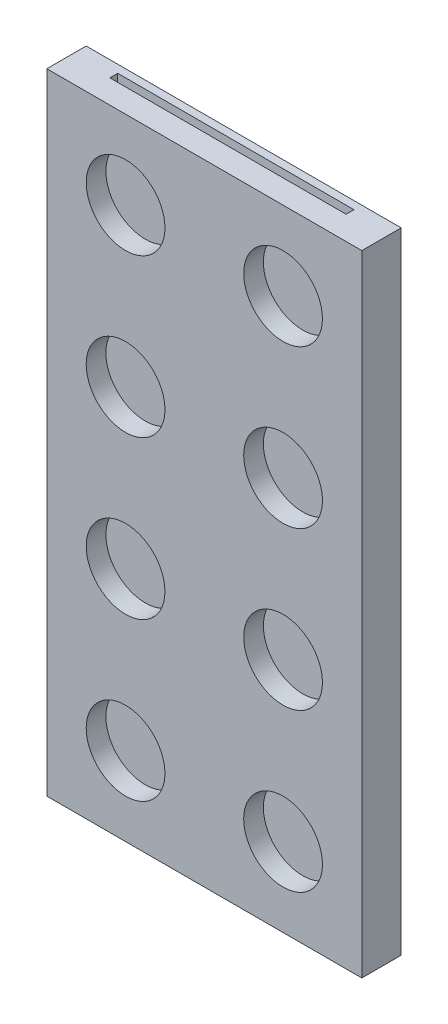
SolidWorks part; units mm, degrees
ref_plane "Front Plane" through (0, 0, 0) normal (0, 0, 1) x (1, 0, 0)
ref_plane "Top Plane" through (0, 0, 0) normal (0, 1, 0) x (1, 0, 0)
ref_plane "Right Plane" through (0, 0, 0) normal (1, 0, 0) x (0, 0, -1)
sketch "Sketch1" plane through (0, 0, 0) normal (0, 0, 1) x (1, 0, 0)
  line L1 (0, 0) -> (50.8, 0)
  line L2 (0, 0) -> (0, 101.6)
  line L3 (0, 101.6) -> (50.8, 101.6)
  line L4 (50.8, 0) -> (50.8, 101.6)
  dimension "D1" = 101.6
  dimension "D2" = 50.8
extrude "Boss-Extrude1" add sketch "Sketch1" along normal blind 6.35
sketch "Sketch3" plane through (0, 0, 6.35) normal (0, 0, 1) x (1, 0, 0)
  line L0 (0, 101.6) -> (0, 0) construction
  line L1 (50.8, 101.6) -> (0, 101.6) construction
  line L2 (0, 0) -> (50.8, 0) construction
  line L3 (25.4, 101.6) -> (25.4, 0)
  line L5 (12.7, 152.4) -> (12.7, 0)
  line L6 (38.1, 101.6) -> (38.1, 0)
  line L7 (50.8, 101.6) -> (50.8, 0)
  line L8 (63.5, 101.6) -> (63.5, 0)
  line L9 (76.2, 101.6) -> (76.2, 0)
  line L10 (88.9, 101.6) -> (88.9, 0)
  line L11 (0, 12.7) -> (50.8, 12.7)
  line L12 (50.8, 0) -> (50.8, 101.6) construction
  line L13 (0, 25.4) -> (50.8, 25.4)
  line L14 (0, 38.1) -> (50.8, 38.1)
  line L15 (0, 50.8) -> (50.8, 50.8)
  line L16 (0, 63.5) -> (50.8, 63.5)
  line L17 (0, 63.6141) -> (50.8, 63.6141)
  line L18 (0, 76.2) -> (50.8, 76.2)
  line L19 (0, 88.9) -> (50.8, 88.9)
  line L20 (0, 101.6) -> (50.8, 101.6)
  line L21 (0, 114.3) -> (50.8, 114.3)
  line L22 (0, 127) -> (50.8, 127)
  line L23 (0, 139.7) -> (50.8, 139.7)
  circle A0 centre (12.7, 139.7) radius 6.35
  circle A2 centre (38.1, 139.7) radius 6.35
  circle A4 centre (63.5, 139.7) radius 2.54
  circle A6 centre (88.9, 139.7) radius 2.54
  circle A7 centre (88.9, 114.3) radius 2.54
  circle A8 centre (63.5, 114.3) radius 2.54
  circle A9 centre (38.1, 114.3) radius 6.35
  circle A10 centre (12.7, 114.3) radius 6.35
  circle A11 centre (88.9, 88.9) radius 2.54
  circle A12 centre (63.5, 88.9) radius 2.54
  circle A13 centre (38.1, 88.9) radius 6.35
  circle A14 centre (12.7, 88.9) radius 6.35
  circle A15 centre (88.9, 63.5) radius 2.54
  circle A16 centre (63.5, 63.5) radius 2.54
  circle A17 centre (38.1, 63.5) radius 6.35
  circle A18 centre (12.7, 63.5) radius 6.35
  circle A19 centre (88.9, 38.1) radius 2.54
  circle A20 centre (63.5, 38.1) radius 2.54
  circle A21 centre (38.1, 38.1) radius 6.35
  circle A22 centre (12.7, 38.1) radius 6.35
  circle A23 centre (88.9, 12.7) radius 2.54
  circle A24 centre (63.5, 12.7) radius 2.54
  circle A25 centre (38.1, 12.7) radius 6.35
  circle A26 centre (12.7, 12.7) radius 6.35
  dimension "D1" = 12.7
  dimension "D2" = 12.7
  dimension "D3" = 12.7
  dimension "D4" = 12.7
  dimension "D5" = 12.7
  dimension "D6" = 12.7
  dimension "D7" = 12.7
  dimension "D8" = 12.7
  dimension "D9" = 12.7
  dimension "D10" = 12.7
  dimension "D11" = 12.7
  dimension "D12" = 12.7
  dimension "D13" = 12.7
  dimension "D14" = 12.7
  dimension "D15" = 12.7
  dimension "D16" = 12.7
  dimension "D17" = 12.7
  dimension "D18" = 12.7
extrude "Cut-Extrude2" cut sketch "Sketch3" against normal blind 3.175 contours A0 | A2 | A4 | A6 | A7 | A8 | A9 | A10 | A14 | A13 | A12 | A11 | A18 | A17 | A16 | A15 | A22 | A21 | A20 | A19 | A26 | A25 | A24 | A23
sketch "Sketch4" plane through (0, 0, 0) normal (0, 0, -1) x (-1, 0, 0)
  line L0 (-44.45, 95.25) -> (-6.35, 95.25)
  line L1 (-6.35, 95.25) -> (-6.35, 6.35)
  line L2 (-6.35, 6.35) -> (-44.45, 6.35)
  line L3 (-44.45, 6.35) -> (-44.45, 95.25)
  line L4 (-50.8, 0) -> (-50.8, 101.6) construction
  line L5 (0, 101.6) -> (0, 0) construction
  line L6 (-50.8, 101.6) -> (0, 101.6) construction
  line L7 (0, 0) -> (-50.8, 0) construction
  dimension "D1" = 6.35
  dimension "D2" = 6.35
  dimension "D3" = 6.35
  dimension "D4" = 6.35
extrude "Cut-Extrude3" cut sketch "Sketch4" against normal blind 2.54
sketch "Sketch5" plane through (0, 101.6, 0) normal (0, 1, 0) x (1, 0, 0)
  line L0 (6.35, -1.27) -> (44.45, -1.27)
  line L1 (44.45, -1.27) -> (44.45, -2.54)
  line L2 (44.45, -2.54) -> (6.35, -2.54)
  line L3 (6.35, -2.54) -> (6.35, -1.27)
  line L4 (0, -6.35) -> (0, 0) construction
  line L5 (50.8, -6.35) -> (50.8, 0) construction
  line L6 (50.8, 0) -> (0, 0) construction
  dimension "D1" = 6.35
  dimension "D2" = 6.35
  dimension "D3" = 1.27
  dimension "D4" = 1.27
extrude "Cut-Extrude4" cut sketch "Sketch5" against normal up to next
